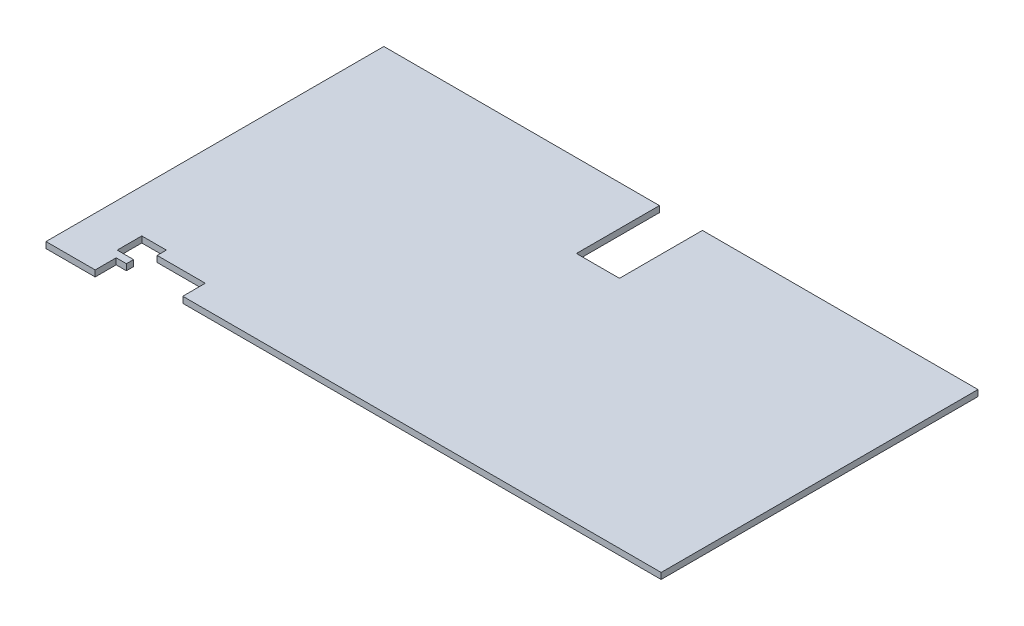
SolidWorks part; units mm, degrees
ref_plane "Front Plane" through (0, 0, 0) normal (0, 0, 1) x (1, 0, 0)
ref_plane "Top Plane" through (0, 0, 0) normal (0, 1, 0) x (1, 0, 0)
ref_plane "Right Plane" through (0, 0, 0) normal (1, 0, 0) x (0, 0, -1)
sketch "Sketch1" plane through (0, 0, 0) normal (0, 1, 0) x (1, 0, 0)
  line L1 (145, 77.325) -> (-145, 77.325)
  line L2 (145, 77.325) -> (145, -77.325)
  line L3 (145, -77.325) -> (-145, -77.325)
  line L4 (-145, 77.325) -> (-145, -77.325)
  line L5 (145, 77.325) -> (-145, -77.325) construction
  line L6 (145, -77.325) -> (-145, 77.325) construction
  point P0 (0, 0)
  dimension "D1" = 154.65
  dimension "D2" = 290
extrude "Boss-Extrude1" add sketch "Sketch1" along normal blind 3
sketch "Sketch2" plane through (0, 3, 0) normal (0, 1, 0) x (1, 0, 0)
  line L0 (145, 77.325) -> (10.5, 77.325)
  line L2 (145, 77.325) -> (-145, 77.325) construction
  line L3 (-145, 77.325) -> (-10.5, 77.325)
  line L4 (10.5, 77.325) -> (10.5, 36.825)
  line L6 (-10.5, 77.325) -> (10.5, 77.325)
  line L7 (-10.5, 77.325) -> (-10.5, 36.825)
  line L8 (-10.5, 36.825) -> (10.5, 36.825)
  line L9 (10.5, 77.325) -> (10.5, 36.825)
  line L10 (-10.5, 77.325) -> (10.5, 36.825) construction
  line L11 (-10.5, 36.825) -> (10.5, 77.325) construction
  point P14 (0, 57.075)
  line M4 (145, 77.325) -> (-145, 77.325)
  dimension "D1" = 134.5
  dimension "D2" = 134.5
  dimension "D3" = 40.5
  dimension "D4" = 40.5
  dimension "D5" = 21
extrude "Cut-Extrude1" cut sketch "Sketch2" against normal through all contours L7 L8 L4 M4
sketch "Sketch3" plane through (0, 3, 0) normal (0, 1, 0) x (1, 0, 0)
  line L0 (-145, -77.325) -> (-116, -77.325)
  line L1 (-145, -77.325) -> (145, -77.325) construction
  line L2 (-116, -77.325) -> (-116, -73.825)
  line L3 (-116, -73.825) -> (-124, -73.825)
  line L4 (-124, -73.825) -> (-124, -61.825)
  line L5 (-124, -61.825) -> (-112, -61.825)
  line L6 (-112, -61.825) -> (-112, -66.325)
  line L7 (-112, -66.325) -> (-88.5, -66.325)
  line L8 (-88.5, -66.325) -> (-88.5, -77.325)
  line L9 (-88.5, -77.325) -> (-116, -77.325)
  line M14 (-145, -77.325) -> (145, -77.325)
  dimension "D1" = 23.5
  dimension "D2" = 27.5
  dimension "D3" = 29
  dimension "D4" = 8
  dimension "D5" = 12
  dimension "D6" = 7.5
  dimension "D7" = 3.5
extrude "Cut-Extrude2" cut sketch "Sketch3" against normal through all contours L8 L7 L6 L5 L4 L3 L2 M14
sketch "Sketch4" plane through (0, 3, 0) normal (0, 1, 0) x (1, 0, 0)
  line L1 (-145, -77.325) -> (-121, -77.325)
  line L2 (-145, -77.325) -> (-145, -87.575)
  line L3 (-145, -87.575) -> (-121, -87.575)
  line L4 (-121, -77.325) -> (-121, -87.575)
  line L5 (-145, -77.325) -> (-121, -87.575) construction
  line L6 (-145, -87.575) -> (-121, -77.325) construction
  point P4 (-133, -82.45)
  dimension "D1" = 10.25
  dimension "D2" = 24
extrude "Boss-Extrude2" add sketch "Sketch4" against normal through all
